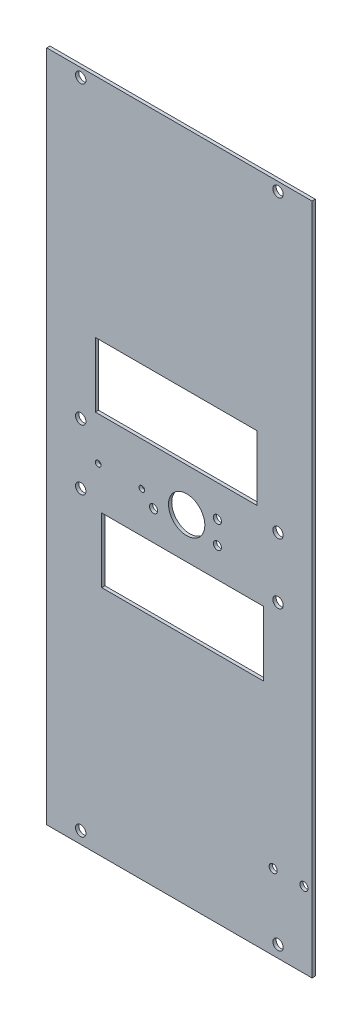
SolidWorks part; units mm, degrees
material "CFRP"
ref_plane "Front Plane" through (0, 0, 0) normal (0, 0, 1) x (1, 0, 0)
ref_plane "Top Plane" through (0, 0, 0) normal (0, 1, 0) x (1, 0, 0)
ref_plane "Right Plane" through (0, 0, 0) normal (1, 0, 0) x (0, 0, -1)
sketch "Sketch1" plane through (0, 0, 0) normal (0, 0, 1) x (1, 0, 0)
  line L1 (41, -104) -> (-41, -104)
  line L2 (41, -104) -> (41, 104)
  line L3 (41, 104) -> (-41, 104)
  line L4 (-41, -104) -> (-41, 104)
  line L5 (41, -104) -> (-41, 104) construction
  line L6 (41, 104) -> (-41, -104) construction
  point P0 (0, 0)
  dimension "D1" = 82
  dimension "D2" = 208
extrude "Boss-Extrude1" add sketch "Sketch1" along normal blind 1
hole_wizard "Ø3.2 (3.2) Diameter Hole1" positions "Sketch3" profile "Sketch2" hole size "Ø3.2" standard "ANSI Metric"
sketch "Sketch3" plane through (0, 0, 1) normal (0, 0, 1) x (1, 0, 0)
  point P0 (-30.5, 10)
  point P2 (30.5, 10)
  point P15 (30.5, -100.3)
  point P17 (-30.5, -100.3)
  point P36 (-30.5, 101.3)
  point P40 (30.5, 101.3)
  point P44 (30.5, -8.7)
  point P45 (30.645, -118.5598)
  point P48 (-30.5, -8.7)
sketch "Sketch2" plane through (-30.5, 10, 1) normal (1, 0, 0) x (0, -1, 0)
  line L0 (0, 0) -> (0, 1)
  line L1 (0, 1) -> (1.6, 1)
  line L2 (1.6, 1) -> (1.6, 0)
  line L5 (1.6, 0) -> (0, 0)
  line L10 (0, 1) -> (-1.6, 1) construction
  line L11 (0, -6.35) -> (0, 107.95) construction
  dimension "Hole Dia." = 3.2
  dimension "Hole Depth" = 1
  dimension "Drill Angle" = 180
sketch "Sketch7" plane through (0, 0, 0) normal (0, 0, -1) x (-1, 0, 0)
  line L0 (-41, -104) -> (-41, 104) construction
  line L1 (24, -12) -> (-26, -12)
  line L2 (24, -12) -> (24, -32)
  line L3 (24, -32) -> (-26, -32)
  line L4 (-26, -12) -> (-26, -32)
  line L5 (41, -104) -> (-41, -104) construction
  line L6 (-24, 14) -> (26, 14)
  line L7 (-24, 14) -> (-24, 34)
  line L8 (-24, 34) -> (26, 34)
  line L9 (26, 14) -> (26, 34)
  line L10 (41, 104) -> (41, -104) construction
  line L11 (-41, 104) -> (41, 104) construction
  dimension "D1" = 50
  dimension "D2" = 20
  dimension "D3" = 15
  dimension "D4" = 72
  dimension "D5" = 50
  dimension "D6" = 20
  dimension "D7" = 15
  dimension "D8" = 70
extrude "Cut-Extrude2" cut sketch "Sketch7" against normal blind 10
hole_wizard "Ø2.5 (2.5) Diameter Hole1" positions "Sketch9" profile "Sketch8" hole size "Ø2.5" standard "ANSI Metric" end condition through all
sketch "Sketch9" plane through (0, 0, 0) normal (0, 0, -1) x (-1, 0, 0)
  point P0 (-29, -80.7028)
  point P3 (-38.5, -80.7028)
sketch "Sketch8" plane through (29, -80.7028, 0) normal (1, 0, 0) x (0, 1, 0)
  line L0 (0, 0) -> (0, 1)
  line L1 (0, 1) -> (1.25, 1)
  line L2 (1.25, 1) -> (1.25, 0)
  line L5 (1.25, 0) -> (0, 0)
  line L11 (0, -6.35) -> (0, 107.95) construction
  dimension "Thru Hole Dia." = 2.5
  dimension "Thru Hole Depth" = 1
hole_wizard "Ø1.75 (1.75) Diameter Hole1" positions "Sketch11" profile "Sketch10" hole size "Ø1.75" standard "ANSI Metric" end condition through all
sketch "Sketch11" plane through (0, 0, 1) normal (0, 0, 1) x (1, 0, 0)
  line L0 (-41, 104) -> (-41, -104) construction
  point P0 (-25.1, 0.65)
  point P2 (-11.6, 0.65)
  dimension "D1" = 15.9
sketch "Sketch10" plane through (-25.1, 0.65, 1) normal (1, 0, 0) x (0, -1, 0)
  line L0 (0, 0) -> (0, 1)
  line L1 (0, 1) -> (0.875, 1)
  line L2 (0.875, 1) -> (0.875, 0)
  line L5 (0.875, 0) -> (0, 0)
  line L11 (0, -6.35) -> (0, 107.95) construction
  dimension "Thru Hole Dia." = 1.75
  dimension "Thru Hole Depth" = 1
sketch "Sketch12" plane through (0, 0, 1) normal (0, 0, 1) x (1, 0, 0)
  line L0 (-41, 104) -> (-41, -104) construction
  circle A0 centre (-8, -2.85) radius 1.25
  circle A1 centre (11.75, -2.85) radius 1.25
  circle A2 centre (11.75, 4.15) radius 1.25
  dimension "D1" = 19.75
  dimension "D2" = 7
  dimension "D3" = 19.75
  dimension "D4" = 33
extrude "Cut-Extrude3" cut sketch "Sketch12" against normal blind 10
sketch "Sketch13" plane through (0, 0, 0) normal (0, 0, -1) x (-1, 0, 0)
  circle A0 centre (-2.25, 0.65) radius 5.6148
extrude "Cut-Extrude4" cut sketch "Sketch13" against normal blind 10
